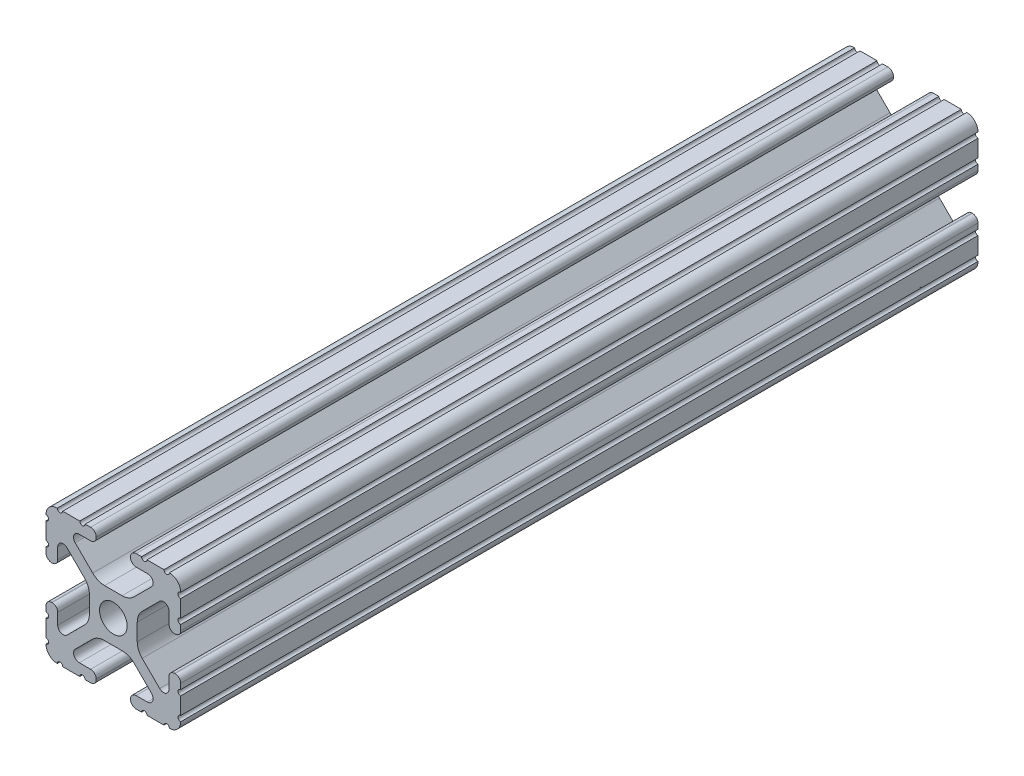
SolidWorks part; units mm, degrees
material "6061 Alloy"
ref_plane "Front Plane" through (0, 0, 0) normal (0, 0, 1) x (1, 0, 0)
ref_plane "Top Plane" through (0, 0, 0) normal (0, 1, 0) x (1, 0, 0)
ref_plane "Right Plane" through (0, 0, 0) normal (1, 0, 0) x (0, 0, -1)
sketch "Sketch1" plane through (0, 0, 0) normal (0, 0, 1) x (1, 0, 0)
  line L88 (-7.1797, -8.6452) -> (-3.9523, -5.4237)
  line L89 (-1.7093, -4.4958) -> (1.7093, -4.4958)
  line L90 (3.9523, -5.4237) -> (7.1797, -8.6452)
  line L91 (6.4164, -10.4902) -> (4.2875, -10.4902)
  line L92 (3.2385, -11.5392) -> (3.2385, -11.651)
  line L93 (4.2875, -12.7) -> (5.3171, -12.7)
  line L94 (6.3331, -12.7) -> (9.5504, -12.7)
  line L95 (12.7, -9.5504) -> (12.7, -6.3331)
  line L96 (12.7, -5.3171) -> (12.7, -4.2875)
  line L97 (11.651, -3.2385) -> (11.5392, -3.2385)
  line L98 (10.4902, -4.2875) -> (10.4902, -6.4021)
  line L99 (8.7371, -7.1294) -> (5.441, -3.8408)
  line L100 (4.5085, -1.5932) -> (4.5085, 1.5932)
  line L101 (5.441, 3.8408) -> (8.7371, 7.1294)
  line L102 (10.4902, 6.4021) -> (10.4902, 4.2875)
  line L103 (11.5392, 3.2385) -> (11.651, 3.2385)
  line L104 (12.7, 4.2875) -> (12.7, 5.3171)
  line L105 (12.7, 6.3331) -> (12.7, 9.5504)
  line L106 (9.5504, 12.7) -> (6.3331, 12.7)
  line L107 (5.3171, 12.7) -> (4.2875, 12.7)
  line L108 (3.2385, 11.651) -> (3.2385, 11.5392)
  line L109 (4.2875, 10.4902) -> (6.4768, 10.4902)
  line L110 (7.207, 8.7244) -> (3.8983, 5.4232)
  line L111 (1.6558, 4.4958) -> (-1.6558, 4.4958)
  line L112 (-3.8983, 5.4232) -> (-7.207, 8.7244)
  line L113 (-6.4768, 10.4902) -> (-4.2875, 10.4902)
  line L114 (-3.2385, 11.5392) -> (-3.2385, 11.651)
  line L115 (-4.2875, 12.7) -> (-5.3171, 12.7)
  line L116 (-6.3331, 12.7) -> (-9.5504, 12.7)
  line L117 (-12.7, 9.5504) -> (-12.7, 6.3331)
  line L118 (-12.7, 5.3171) -> (-12.7, 4.2875)
  line L119 (-11.651, 3.2385) -> (-11.5392, 3.2385)
  line L120 (-10.4902, 4.2875) -> (-10.4902, 6.4021)
  line L121 (-8.7371, 7.1294) -> (-5.441, 3.8408)
  line L122 (-4.5085, 1.5932) -> (-4.5085, -1.5932)
  line L123 (-5.441, -3.8408) -> (-8.7371, -7.1294)
  line L124 (-10.4902, -6.4021) -> (-10.4902, -4.2875)
  line L125 (-11.5392, -3.2385) -> (-11.651, -3.2385)
  line L126 (-12.7, -4.2875) -> (-12.7, -5.3171)
  line L127 (-12.7, -6.3331) -> (-12.7, -9.5504)
  line L128 (-9.5504, -12.7) -> (-6.3331, -12.7)
  line L129 (-5.3171, -12.7) -> (-4.2875, -12.7)
  line L130 (-3.2385, -11.651) -> (-3.2385, -11.5392)
  line L131 (-4.2875, -10.4902) -> (-6.4164, -10.4902)
  circle A1 centre (0, 0) radius 2.6035
  arc A104 (-7.1797, -8.6452) -> (-6.4164, -10.4902) centre (-6.4164, -9.4098) ccw
  arc A105 (-1.7093, -4.4958) -> (-3.9523, -5.4237) centre (-1.7093, -7.6708) ccw
  arc A106 (3.9523, -5.4237) -> (1.7093, -4.4958) centre (1.7093, -7.6708) ccw
  arc A107 (6.4164, -10.4902) -> (7.1797, -8.6452) centre (6.4164, -9.4098) ccw
  arc A108 (4.2875, -10.4902) -> (3.2385, -11.5392) centre (4.2875, -11.5392) ccw
  arc A109 (3.2385, -11.651) -> (4.2875, -12.7) centre (4.2875, -11.651) ccw
  arc A110 (6.3331, -12.7) -> (5.3171, -12.7) centre (5.8251, -12.7) ccw
  arc A111 (10.5664, -12.6998) -> (9.5504, -12.7) centre (10.0584, -12.7) ccw
  arc A112 (10.5664, -12.6998) -> (12.6998, -10.5664) centre (10.5918, -10.5918) ccw
  arc A113 (12.7, -9.5504) -> (12.6998, -10.5664) centre (12.7, -10.0584) ccw
  arc A114 (12.7, -5.3171) -> (12.7, -6.3331) centre (12.7, -5.8251) ccw
  arc A115 (12.7, -4.2875) -> (11.651, -3.2385) centre (11.651, -4.2875) ccw
  arc A116 (11.5392, -3.2385) -> (10.4902, -4.2875) centre (11.5392, -4.2875) ccw
  arc A117 (8.7371, -7.1294) -> (10.4902, -6.4021) centre (9.4628, -6.4021) ccw
  arc A118 (4.5085, -1.5932) -> (5.441, -3.8408) centre (7.6835, -1.5932) ccw
  arc A119 (5.441, 3.8408) -> (4.5085, 1.5932) centre (7.6835, 1.5932) ccw
  arc A120 (10.4902, 6.4021) -> (8.7371, 7.1294) centre (9.4628, 6.4021) ccw
  arc A121 (10.4902, 4.2875) -> (11.5392, 3.2385) centre (11.5392, 4.2875) ccw
  arc A122 (11.651, 3.2385) -> (12.7, 4.2875) centre (11.651, 4.2875) ccw
  arc A123 (12.7, 6.3331) -> (12.7, 5.3171) centre (12.7, 5.8251) ccw
  arc A124 (12.6998, 10.5664) -> (12.7, 9.5504) centre (12.7, 10.0584) ccw
  arc A125 (12.6998, 10.5664) -> (10.5664, 12.6998) centre (10.5918, 10.5918) ccw
  arc A126 (9.5504, 12.7) -> (10.5664, 12.6998) centre (10.0584, 12.7) ccw
  arc A127 (5.3171, 12.7) -> (6.3331, 12.7) centre (5.8251, 12.7) ccw
  arc A128 (4.2875, 12.7) -> (3.2385, 11.651) centre (4.2875, 11.651) ccw
  arc A129 (3.2385, 11.5392) -> (4.2875, 10.4902) centre (4.2875, 11.5392) ccw
  arc A130 (7.207, 8.7244) -> (6.4768, 10.4902) centre (6.4768, 9.4563) ccw
  arc A131 (1.6558, 4.4958) -> (3.8983, 5.4232) centre (1.6558, 7.6708) ccw
  arc A132 (-3.8983, 5.4232) -> (-1.6558, 4.4958) centre (-1.6558, 7.6708) ccw
  arc A133 (-6.4768, 10.4902) -> (-7.207, 8.7244) centre (-6.4768, 9.4563) ccw
  arc A134 (-4.2875, 10.4902) -> (-3.2385, 11.5392) centre (-4.2875, 11.5392) ccw
  arc A135 (-3.2385, 11.651) -> (-4.2875, 12.7) centre (-4.2875, 11.651) ccw
  arc A136 (-6.3331, 12.7) -> (-5.3171, 12.7) centre (-5.8251, 12.7) ccw
  arc A137 (-10.5664, 12.6998) -> (-9.5504, 12.7) centre (-10.0584, 12.7) ccw
  arc A138 (-10.5664, 12.6998) -> (-12.6998, 10.5664) centre (-10.5918, 10.5918) ccw
  arc A139 (-12.7, 9.5504) -> (-12.6998, 10.5664) centre (-12.7, 10.0584) ccw
  arc A140 (-12.7, 5.3171) -> (-12.7, 6.3331) centre (-12.7, 5.8251) ccw
  arc A141 (-12.7, 4.2875) -> (-11.651, 3.2385) centre (-11.651, 4.2875) ccw
  arc A142 (-11.5392, 3.2385) -> (-10.4902, 4.2875) centre (-11.5392, 4.2875) ccw
  arc A143 (-8.7371, 7.1294) -> (-10.4902, 6.4021) centre (-9.4628, 6.4021) ccw
  arc A144 (-4.5085, 1.5932) -> (-5.441, 3.8408) centre (-7.6835, 1.5932) ccw
  arc A145 (-5.441, -3.8408) -> (-4.5085, -1.5932) centre (-7.6835, -1.5932) ccw
  arc A146 (-10.4902, -6.4021) -> (-8.7371, -7.1294) centre (-9.4628, -6.4021) ccw
  arc A147 (-10.4902, -4.2875) -> (-11.5392, -3.2385) centre (-11.5392, -4.2875) ccw
  arc A148 (-11.651, -3.2385) -> (-12.7, -4.2875) centre (-11.651, -4.2875) ccw
  arc A149 (-12.7, -6.3331) -> (-12.7, -5.3171) centre (-12.7, -5.8251) ccw
  arc A150 (-12.6998, -10.5664) -> (-12.7, -9.5504) centre (-12.7, -10.0584) ccw
  arc A151 (-12.6998, -10.5664) -> (-10.5664, -12.6998) centre (-10.5918, -10.5918) ccw
  arc A152 (-9.5504, -12.7) -> (-10.5664, -12.6998) centre (-10.0584, -12.7) ccw
  arc A153 (-5.3171, -12.7) -> (-6.3331, -12.7) centre (-5.8251, -12.7) ccw
  arc A154 (-4.2875, -12.7) -> (-3.2385, -11.651) centre (-4.2875, -11.651) ccw
  arc A155 (-3.2385, -11.5392) -> (-4.2875, -10.4902) centre (-4.2875, -11.5392) ccw
extrude "Boss-Extrude1" add sketch "Sketch1" along normal mid plane 150.368
